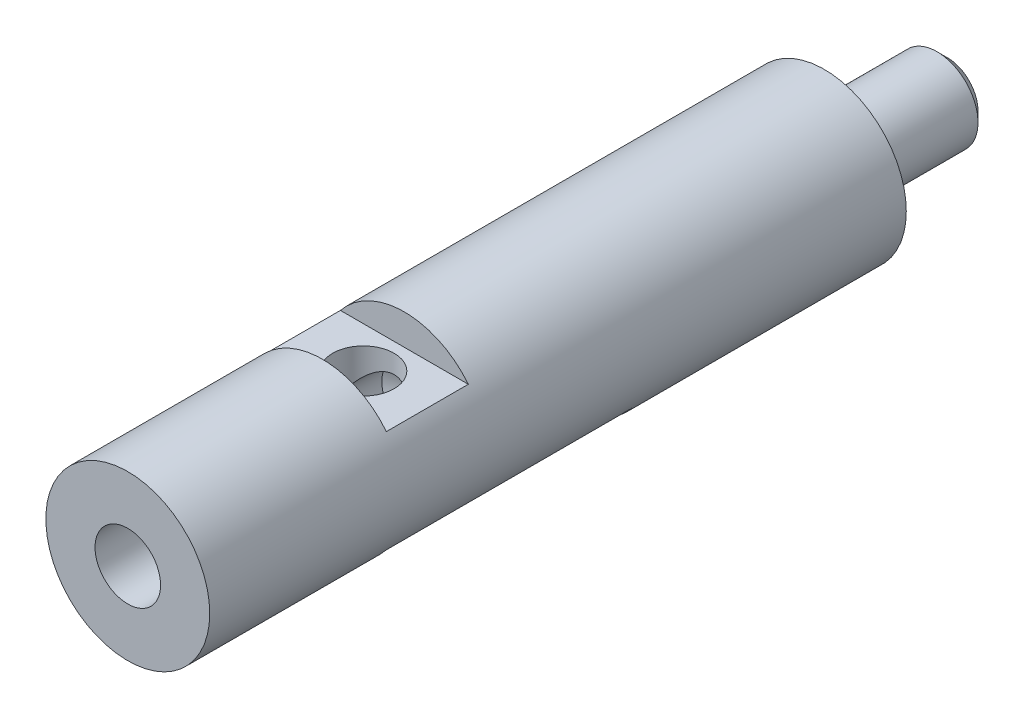
SolidWorks part; units mm, degrees
ref_plane "Ön Düzlem" through (0, 0, 0) normal (0, 0, 1) x (1, 0, 0)
ref_plane "Üst Düzlem" through (0, 0, 0) normal (0, 1, 0) x (1, 0, 0)
ref_plane "Sağ Düzlem" through (0, 0, 0) normal (1, 0, 0) x (0, 0, -1)
sketch "Sketch1" plane through (0, 0, 0) normal (0, 0, 1) x (1, 0, 0)
  circle A0 centre (0, 0) radius 4
  dimension "D1" = 8
extrude "Boss-Extrude2" add sketch "Sketch1" against normal blind 34
sketch "Sketch2" plane through (0, 0, -34) normal (0, 0, -1) x (-1, 0, 0)
  circle A0 centre (0, 0) radius 2
extrude "Boss-Extrude3" add sketch "Sketch2" along normal blind 6
chamfer "Chamfer1" distance 0.5 angle 45 1 edges at (-2, 0, -40)
hole_wizard "Ø3.2 (3.2) Diameter Hole1" positions "Sketch3" profile "Sketch4" hole size "Ø3.2" standard "ANSI Metric"
sketch "Sketch3" plane through (0, 0, 0) normal (0, 0, 1) x (1, 0, 0)
  point P0 (0, 0)
sketch "Sketch4" plane through (0, 0, 0) normal (1, 0, 0) x (0, -1, 0)
  line L0 (0, 0) -> (0, 14.9614)
  line L1 (0, 14.9614) -> (1.6, 14)
  line L2 (1.6, 14) -> (1.6, 0)
  line L5 (1.6, 0) -> (0, 0)
  line L10 (0, 14.9614) -> (-1.6, 14) construction
  line L11 (0, -6.35) -> (0, 107.95) construction
  dimension "Hole Dia." = 3.2
  dimension "Hole Depth" = 14
  dimension "Drill Angle" = 118
sketch "Sketch5" plane through (0, 0, 0) normal (1, 0, 0) x (0, 0, -1)
  line L0 (0, -4) -> (34, -4) construction
  line L1 (9.5, -2.5) -> (21.5, -2.5)
  line L2 (9.5, -2.5) -> (9.5, -4)
  line L3 (9.5, -4) -> (21.5, -4)
  line L4 (21.5, -2.5) -> (21.5, -4)
  line L5 (34, 4) -> (0, 4) construction
  line L6 (9.5, 4) -> (13.5, 4)
  line L7 (9.5, 4) -> (9.5, 2.5)
  line L8 (9.5, 2.5) -> (13.5, 2.5)
  line L9 (13.5, 4) -> (13.5, 2.5)
  line L10 (0, 4) -> (0, -4) construction
  dimension "D1" = 1.5
  dimension "D2" = 12
  dimension "D3" = 1.5
  dimension "D4" = 4
  dimension "D5" = 9.5
extrude "Cut-Extrude1" cut sketch "Sketch5" against normal through all both and the other way through all
hole_wizard "Ø3.0 (3) Diameter Hole1" positions "Sketch6" profile "Sketch7" hole size "Ø3.0" standard "ANSI Metric"
sketch "Sketch6" plane through (0, 2.5, 0) normal (0, 1, 0) x (1, 0, 0)
  line L0 (-3.1225, 9.5) -> (3.1225, 13.5) construction
  point P9 (0, 11.5)
sketch "Sketch7" plane through (0, 2.5, -11.5) normal (1, 0, 0) x (0, 0, 1)
  line L0 (0, 0) -> (0, 0.9)
  line L1 (0, 0.9) -> (1.5, 0.9)
  line L2 (1.5, 0.9) -> (1.5, 0)
  line L5 (1.5, 0) -> (0, 0)
  line L11 (0, -6.35) -> (0, 107.95) construction
  dimension "Thru Hole Dia." = 3
  dimension "Thru Hole Depth" = 0.9
scale "Scale1" scale about centroid uniform scaling yes scale factor 1.5
